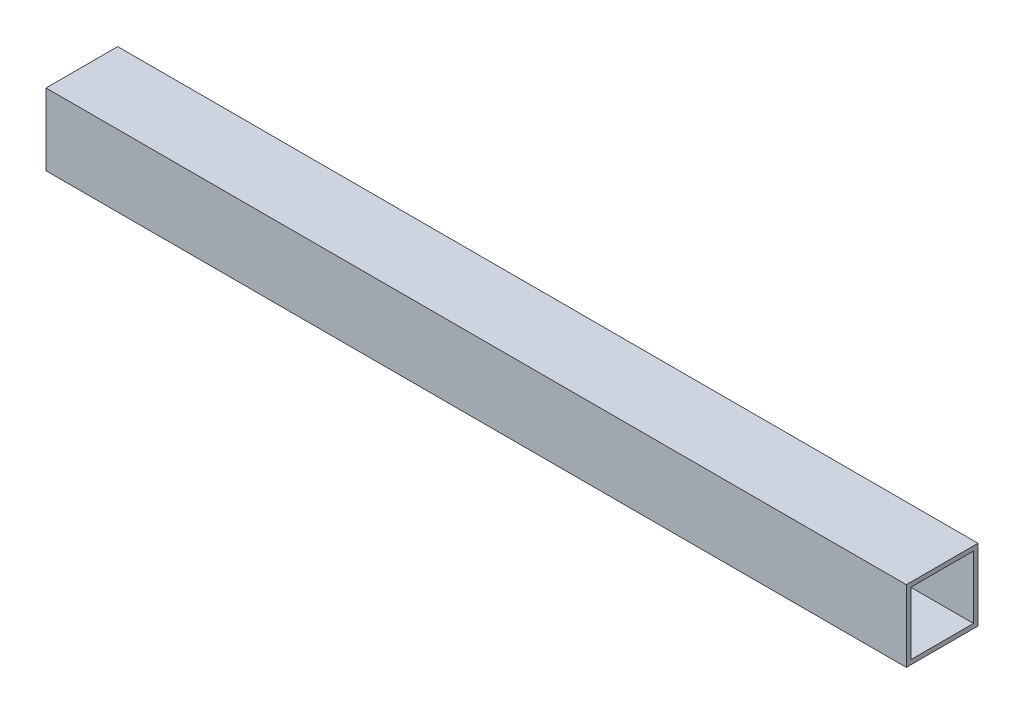
SolidWorks part; units mm, degrees
ref_plane "Front Plane" through (0, 0, 0) normal (0, 0, 1) x (1, 0, 0)
ref_plane "Top Plane" through (0, 0, 0) normal (0, 1, 0) x (1, 0, 0)
ref_plane "Right Plane" through (0, 0, 0) normal (1, 0, 0) x (0, 0, -1)
sketch "Sketch1" plane through (0, 0, 0) normal (1, 0, 0) x (0, 0, -1)
  line L1 (-16.1153, 20.2529) -> (9.2847, 20.2529)
  line L2 (-16.1153, 20.2529) -> (-16.1153, -5.1471)
  line L3 (-16.1153, -5.1471) -> (9.2847, -5.1471)
  line L4 (9.2847, 20.2529) -> (9.2847, -5.1471)
  dimension "D1" = 25.4
  dimension "D2" = 25.4
extrude "Boss-Extrude1" add sketch "Sketch1" along normal blind 304.8
sketch "Sketch2" plane through (0, 0, 0) normal (-1, 0, 0) x (0, 0, 1)
  line L0 (-9.2847, 20.2529) -> (16.1153, 20.2529) construction
  line L1 (-7.6972, 18.6654) -> (14.5278, 18.6654)
  line L2 (-7.6972, 18.6654) -> (-7.6972, -3.5596)
  line L3 (-7.6972, -3.5596) -> (14.5278, -3.5596)
  line L4 (14.5278, 18.6654) -> (14.5278, -3.5596)
  line L5 (-7.6972, 18.6654) -> (14.5278, -3.5596) construction
  line L6 (-7.6972, -3.5596) -> (14.5278, 18.6654) construction
  line L7 (16.1153, 20.2529) -> (16.1153, -5.1471) construction
  point P0 (3.4153, 7.5529)
  point P5 (0, 0)
  point P6 (2.936, 7.3774)
  point P7 (0, 0)
  point P8 (3.511, 7.4253)
  point P11 (0, 0)
  dimension "D1" = 1.5875
  dimension "D2" = 1.5875
extrude "Cut-Extrude1" cut sketch "Sketch2" against normal through all
